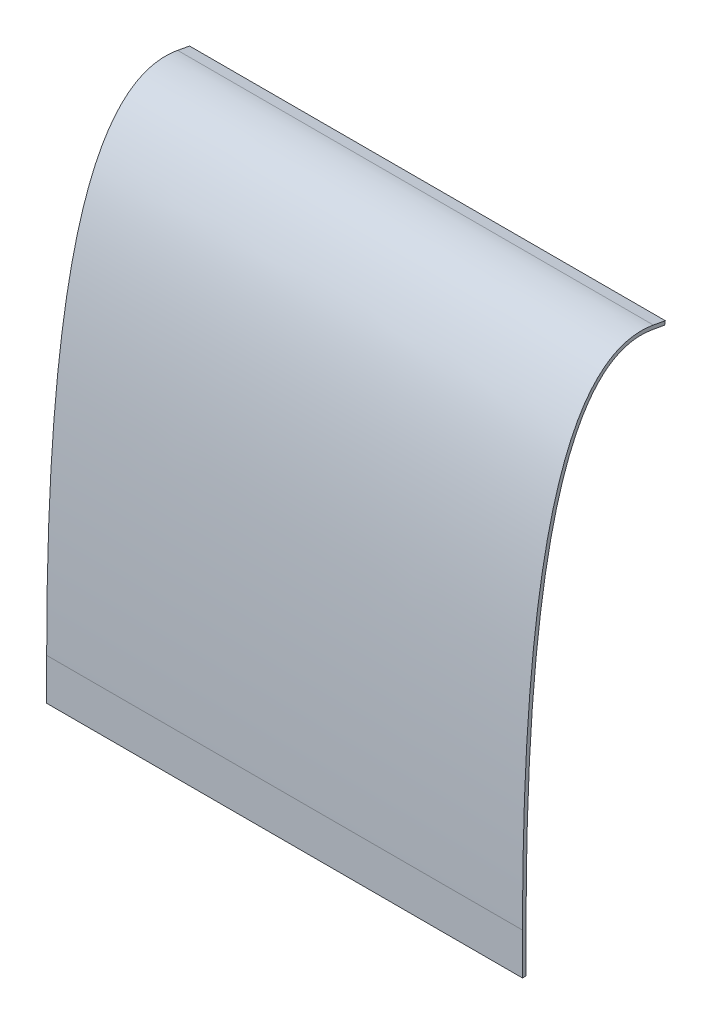
SolidWorks part; units mm, degrees
material "ABS"
ref_plane "Front Plane" through (0, 0, 0) normal (0, 0, 1) x (1, 0, 0)
ref_plane "Top Plane" through (0, 0, 0) normal (0, 1, 0) x (1, 0, 0)
ref_plane "Right Plane" through (0, 0, 0) normal (1, 0, 0) x (0, 0, -1)
sketch "Sketch1" plane through (0, 0, 0) normal (0, 0, 1) x (1, 0, 0)
  line L1 (0, -5374.6538) -> (418.0789, -5374.6538)
  line L2 (0, -5374.6538) -> (0, -5338.1688)
  line L3 (0, -5338.1688) -> (418.0789, -5338.1688)
  line L4 (418.0789, -5374.6538) -> (418.0789, -5338.1688)
extrude "Boss-Extrude1" add sketch "Sketch1" along normal blind 3.175
sketch "Sketch7" plane through (0, 0, 0) normal (-1, 0, 0) x (0, 0, 1)
  line L0 (-111.3306, -4938.4211) -> (-121.7981, -4940.3387) construction
  line L1 (-111.3306, -4938.4211) -> (-121.7981, -4940.3387)
  line L2 (-111.9027, -4935.2981) -> (-122.3702, -4937.2157)
  line L3 (0, -5338.1688) -> (3.175, -5338.1688)
  line L4 (-121.7981, -4940.3387) -> (-122.3702, -4937.2157)
  parabola Q1 (0, -5338.1688) -> (-111.3306, -4938.4211) focus (-95.1822, -4961.5309) apex (-89.4683, -4938.9209) construction
  parabola Q2 (0, -5338.1688) -> (-111.3306, -4938.4211) focus (-95.1822, -4961.5309) apex (-89.4683, -4938.9209)
  spline S0 degree 1 poles (3.175, -5338.1688) (-111.9027, -4935.2981) knots 0 0 1 1 construction
  spline S1 degree 3 poles (3.175, -5338.1688) (3.175, -5335.9873) (3.1705, -5331.6114) (3.1433, -5322.9634) (3.0752, -5312.2764) (2.9392, -5299.6714) (2.6852, -5283.1493) (2.2316, -5263.0336) (1.4695, -5239.7527) (0.4894, -5217.3296) (-1.108, -5188.5757) (-3.6502, -5154.7763) (-7.5749, -5117.6426) (-12.3759, -5083.9302) (-18.0569, -5053.6329) (-26.8143, -5017.7793) (-37.3605, -4988.7186) (-49.7958, -4966.3989) (-60.1213, -4953.0273) (-71.513, -4943.0587) (-81.9237, -4937.6808) (-90.7534, -4935.2066) (-97.598, -4934.2716) (-103.4746, -4934.2595) (-108.2539, -4934.7015) (-110.6968, -4935.0772) (-111.9027, -4935.2981) knots 0.490445 0.490445 0.490445 0.490445 0.490529 0.490612 0.490779 0.490945 0.491112 0.491445 0.491778 0.492111 0.492444 0.49311 0.493776 0.494442 0.495108 0.495775 0.497107 0.497773 0.498439 0.499105 0.499771 0.500104 0.500437 0.500771 0.500937 0.501104 0.501104 0.501104 0.501104
  dimension "D1" = 3.175
sweep "Sweep1" add profiles "Sketch7" path edge at (209.0395, -5338.1688, 0)
